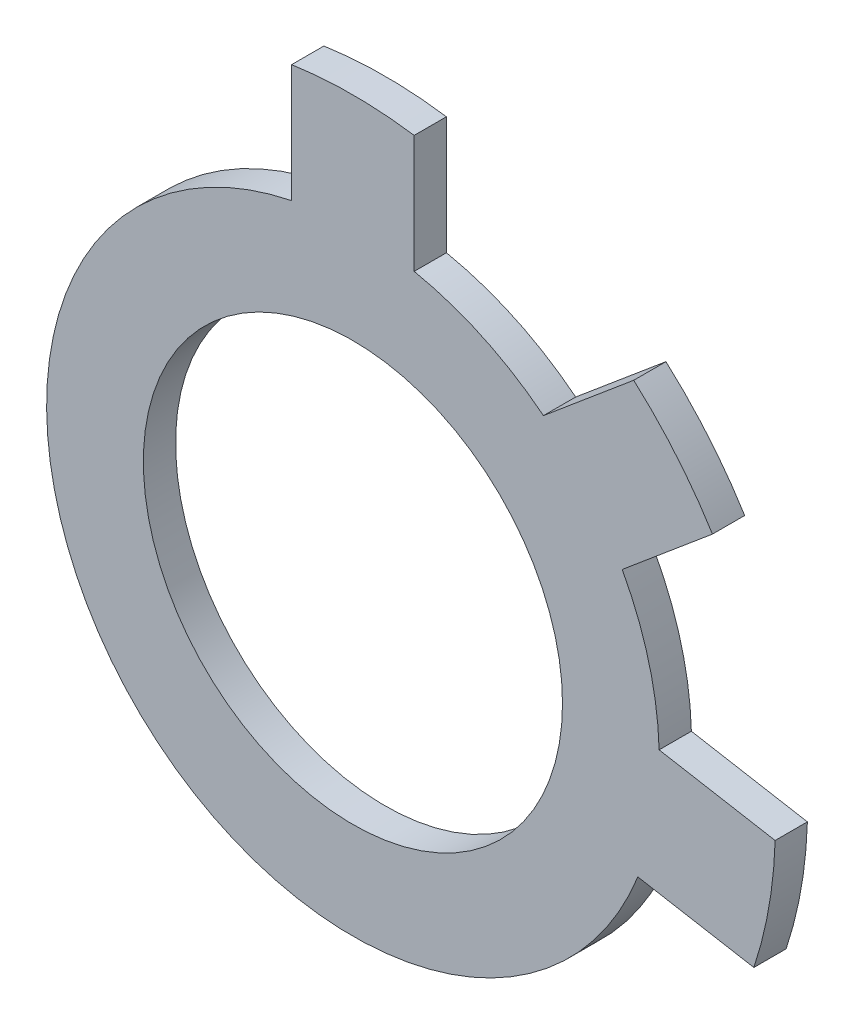
SolidWorks part; units mm, degrees
ref_plane "前视基准面" through (0, 0, 0) normal (0, 0, 1) x (1, 0, 0)
ref_plane "上视基准面" through (0, 0, 0) normal (0, 1, 0) x (1, 0, 0)
ref_plane "右视基准面" through (0, 0, 0) normal (1, 0, 0) x (0, 0, -1)
sketch "草图1" plane through (0, 0, 0) normal (0, 0, 1) x (1, 0, 0)
  line L0 (0, 0) -> (0, 20.0295) construction
  line L1 (8.3517, 4.5276) -> (11.1504, 6.876)
  line L2 (5.9091, 7.4386) -> (8.7078, 9.787)
  line L3 (-1.9, 9.3081) -> (-1.9, 12.9615)
  line L4 (8.8367, -3.4875) -> (12.4346, -4.1219)
  line L5 (9.4966, 0.2548) -> (13.0945, -0.3796)
  line L6 (1.9, 9.3081) -> (1.9, 12.9615)
  arc A0 (11.1504, 6.876) -> (8.7078, 9.787) centre (0, 0) ccw
  circle A1 centre (0, 0) radius 6.5
  arc A2 (-1.9, 9.3081) -> (8.8367, -3.4875) centre (0, 0) ccw
  arc A3 (1.9, 12.9615) -> (-1.9, 12.9615) centre (0, 0) ccw
  arc A4 (12.4346, -4.1219) -> (13.0945, -0.3796) centre (0, 0) ccw
  arc A5 (5.9091, 7.4386) -> (1.9, 9.3081) centre (0, 0) ccw
  arc A6 (9.4966, 0.2548) -> (8.3517, 4.5276) centre (0, 0) ccw
  point P5 (1.9, 0)
  point P7 (1.9, 20.0295)
  point P8 (-1.9, 0)
  point P9 (-1.9, 20.0295)
  dimension "D1" = 13
  dimension "D3" = 19
extrude "拉伸1" add sketch "草图1" along normal blind 1
